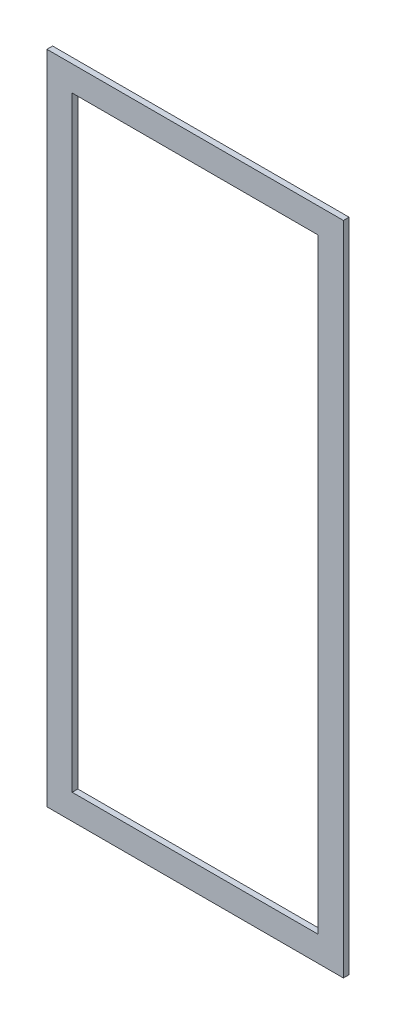
SolidWorks part; units mm, degrees
material "VITON"
ref_plane "Plano frontal" through (0, 0, 0) normal (0, 0, 1) x (1, 0, 0)
ref_plane "Plano superior" through (0, 0, 0) normal (0, 1, 0) x (1, 0, 0)
ref_plane "Plano direito" through (0, 0, 0) normal (1, 0, 0) x (0, 0, -1)
sketch "Esboço1" plane through (0, 0, 0) normal (0, 0, 1) x (1, 0, 0)
  line L1 (-47, -104) -> (47, -104)
  line L2 (-47, -104) -> (-47, 104)
  line L3 (-47, 104) -> (47, 104)
  line L4 (47, -104) -> (47, 104)
  line L5 (-47, -104) -> (47, 104) construction
  line L6 (-47, 104) -> (47, -104) construction
  line L7 (-39, -96) -> (39, -96)
  line L8 (-39, -96) -> (-39, 96)
  line L9 (-39, 96) -> (39, 96)
  line L10 (39, -96) -> (39, 96)
  line L11 (-39, -96) -> (39, 96) construction
  line L12 (-39, 96) -> (39, -96) construction
  point P0 (0, 0)
  point P6 (0, 0)
  dimension "D1" = 94
  dimension "D2" = 208
  dimension "D3" = 8
  dimension "D4" = 8
extrude "Ressalto-extrusão1" add sketch "Esboço1" along normal blind 1.8
